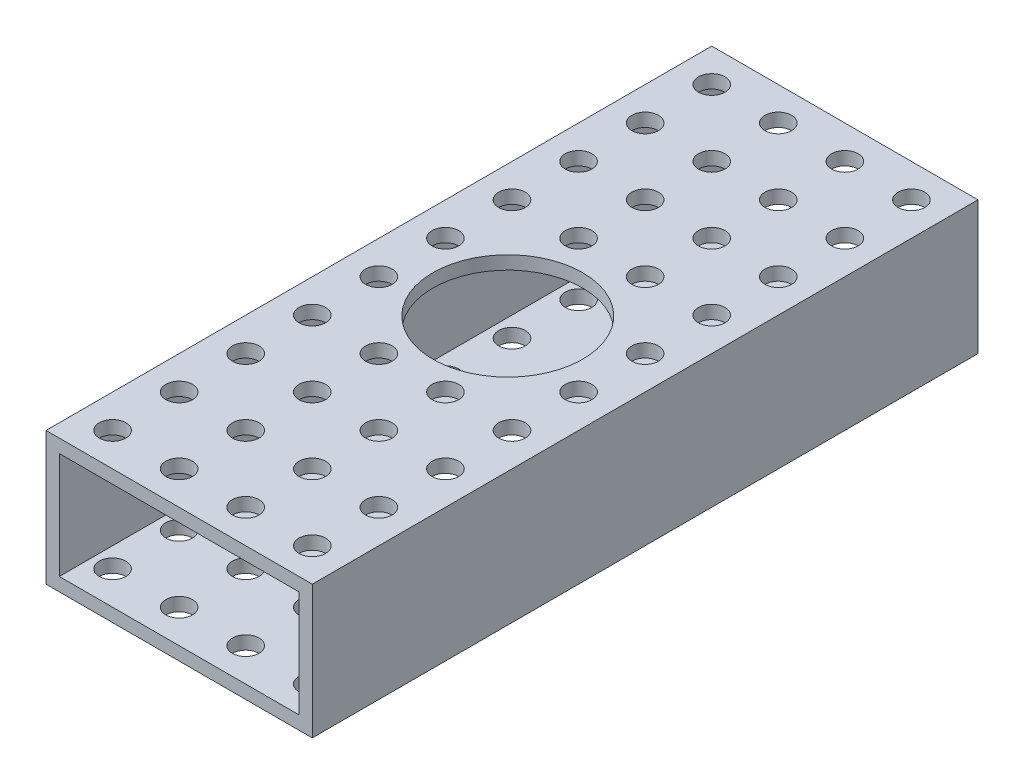
SolidWorks part; units mm, degrees
ref_plane "Front Plane" through (0, 0, 0) normal (0, 0, 1) x (1, 0, 0)
ref_plane "Top Plane" through (0, 0, 0) normal (0, 1, 0) x (1, 0, 0)
ref_plane "Right Plane" through (0, 0, 0) normal (1, 0, 0) x (0, 0, -1)
sketch "Sketch1" plane through (0, 0, 0) normal (0, 0, 1) x (1, 0, 0)
  line L1 (-100.584, 60.9405) -> (-49.784, 60.9405)
  line L2 (-100.584, 60.9405) -> (-100.584, 86.3405)
  line L3 (-100.584, 86.3405) -> (-49.784, 86.3405)
  line L4 (-49.784, 60.9405) -> (-49.784, 86.3405)
  line L5 (-100.584, 60.9405) -> (-49.784, 86.3405) construction
  line L6 (-100.584, 86.3405) -> (-49.784, 60.9405) construction
  line L7 (-98.044, 63.4805) -> (-52.324, 63.4805)
  line L8 (-98.044, 63.4805) -> (-98.044, 83.8005)
  line L9 (-98.044, 83.8005) -> (-52.324, 83.8005)
  line L10 (-52.324, 63.4805) -> (-52.324, 83.8005)
  line L11 (-98.044, 63.4805) -> (-52.324, 83.8005) construction
  line L12 (-98.044, 83.8005) -> (-52.324, 63.4805) construction
  point P0 (-75.184, 73.6405)
  point P5 (-75.184, 73.6405)
  dimension "D1" = 45.72
  dimension "D2" = 50.8
  dimension "D3" = 25.4
  dimension "D4" = 20.32
extrude "Boss-Extrude1" add sketch "Sketch1" along normal blind 127
sketch "Sketch2" plane through (0, 86.3405, 0) normal (0, 1, 0) x (1, 0, 0)
  line L0 (-49.784, 0) -> (-100.584, 0) construction
  line L1 (-100.584, -127) -> (-100.584, 0) construction
  circle A0 centre (-94.234, -6.35) radius 2.54
  circle A1 centre (-81.534, -6.35) radius 2.54
  circle A2 centre (-68.834, -6.35) radius 2.54
  circle A3 centre (-56.134, -6.35) radius 2.54
  circle A4 centre (-81.534, -19.05) radius 2.54
  circle A5 centre (-68.834, -19.05) radius 2.54
  circle A6 centre (-56.134, -19.05) radius 2.54
  circle A7 centre (-81.534, -31.75) radius 2.54
  circle A8 centre (-68.834, -31.75) radius 2.54
  circle A9 centre (-56.134, -31.75) radius 2.54
  circle A10 centre (-81.534, -44.45) radius 2.54
  circle A11 centre (-68.834, -44.45) radius 2.54
  circle A12 centre (-56.134, -44.45) radius 2.54
  circle A13 centre (-81.534, -57.15) radius 2.54
  circle A14 centre (-68.834, -57.15) radius 2.54
  circle A15 centre (-56.134, -57.15) radius 2.54
  circle A16 centre (-81.534, -69.85) radius 2.54
  circle A17 centre (-68.834, -69.85) radius 2.54
  circle A18 centre (-56.134, -69.85) radius 2.54
  circle A19 centre (-81.534, -82.55) radius 2.54
  circle A20 centre (-68.834, -82.55) radius 2.54
  circle A21 centre (-56.134, -82.55) radius 2.54
  circle A22 centre (-81.534, -95.25) radius 2.54
  circle A23 centre (-68.834, -95.25) radius 2.54
  circle A24 centre (-56.134, -95.25) radius 2.54
  circle A25 centre (-81.534, -107.95) radius 2.54
  circle A26 centre (-68.834, -107.95) radius 2.54
  circle A27 centre (-56.134, -107.95) radius 2.54
  circle A28 centre (-81.534, -120.65) radius 2.54
  circle A29 centre (-68.834, -120.65) radius 2.54
  circle A30 centre (-56.134, -120.65) radius 2.54
  circle A31 centre (-94.234, -19.05) radius 2.54
  circle A32 centre (-94.234, -31.75) radius 2.54
  circle A33 centre (-94.234, -44.45) radius 2.54
  circle A34 centre (-94.234, -57.15) radius 2.54
  circle A35 centre (-94.234, -69.85) radius 2.54
  circle A36 centre (-94.234, -82.55) radius 2.54
  circle A37 centre (-94.234, -95.25) radius 2.54
  circle A38 centre (-94.234, -107.95) radius 2.54
  circle A39 centre (-94.234, -120.65) radius 2.54
  dimension "D1" = 6.35
  dimension "D2" = 6.35
  dimension "D3" = 4
  dimension "D4" = 10
extrude "Cut-Extrude1" cut sketch "Sketch2" against normal blind 25.4
sketch "Sketch3" plane through (0, 60.9405, 0) normal (0, -1, 0) x (1, 0, 0)
  circle A0 centre (-75.4506, 64.0363) radius 14.3002 construction
  circle A1 centre (-75.4506, 64.0363) radius 14.3002
extrude "Cut-Extrude2" cut sketch "Sketch3" against normal blind 25.4
